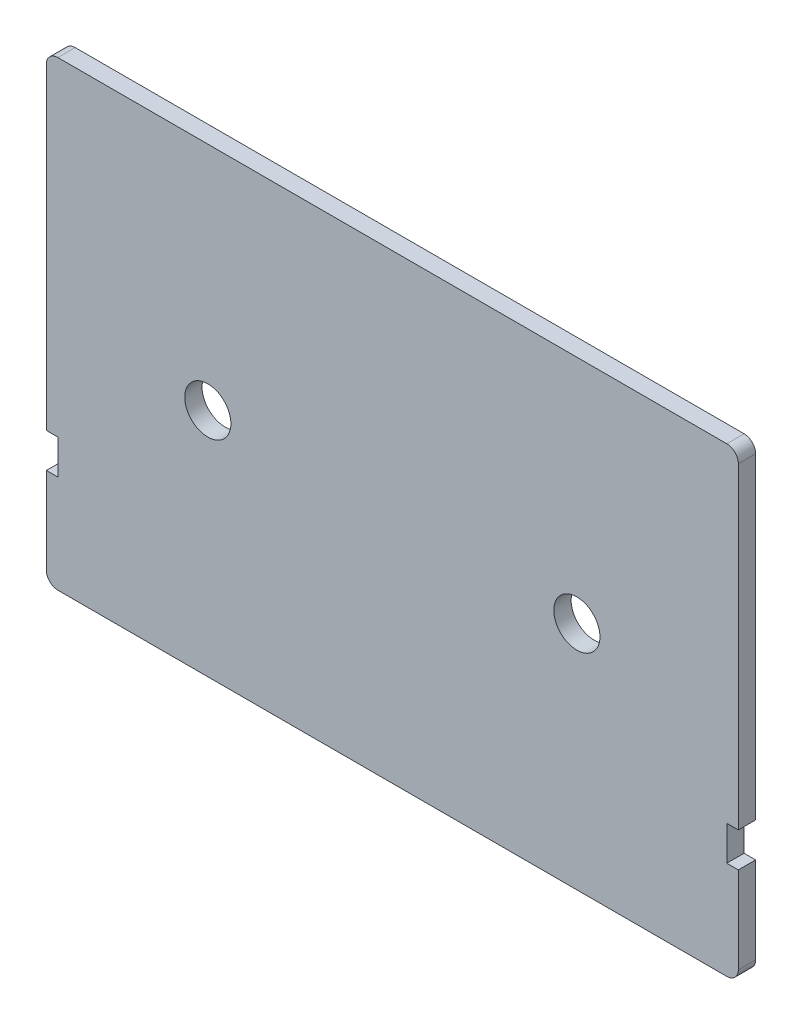
SolidWorks part; units mm, degrees
ref_plane "前视基准面" through (0, 0, 0) normal (0, 0, 1) x (1, 0, 0)
ref_plane "上视基准面" through (0, 0, 0) normal (0, 1, 0) x (1, 0, 0)
ref_plane "右视基准面" through (0, 0, 0) normal (1, 0, 0) x (0, 0, -1)
sketch "草图1" plane through (0, 0, 0) normal (0, 0, 1) x (1, 0, 0)
  line L1 (30, -20) -> (-30, -20)
  line L2 (30, -20) -> (30, 20)
  line L3 (30, 20) -> (-30, 20)
  line L4 (-30, -20) -> (-30, 20)
  line L5 (30, -20) -> (-30, 20) construction
  line L6 (30, 20) -> (-30, -20) construction
  point P0 (0, 0)
  dimension "D1" = 60
  dimension "D2" = 40
extrude "凸台-拉伸1" add sketch "草图1" along normal blind 1.5
sketch "草图3" plane through (0, 0, 1.5) normal (0, 0, 1) x (1, 0, 0)
  circle A0 centre (-16, 0) radius 2
  circle A1 centre (16, 0) radius 2
  point P4 (0, 0)
  dimension "D1" = 4
  dimension "D2" = 4
  dimension "D3" = 16
  dimension "D4" = 16
extrude "切除-拉伸1" cut sketch "草图3" against normal blind 10
sketch "草图4" plane through (0, 0, 1.5) normal (0, 0, 1) x (1, 0, 0)
  line L0 (-30, 20) -> (-30, -20) construction
  line L1 (-30, -11.5) -> (-29, -11.5)
  line L2 (-30, -11.5) -> (-30, -8.5)
  line L3 (-30, -8.5) -> (-29, -8.5)
  line L4 (-29, -11.5) -> (-29, -8.5)
  line L5 (-30, -11.5) -> (-29, -8.5) construction
  line L6 (-30, -8.5) -> (-29, -11.5) construction
  line L7 (30, -20) -> (30, 20) construction
  line L8 (30, -11.5) -> (29, -11.5)
  line L9 (30, -11.5) -> (30, -8.5)
  line L10 (30, -8.5) -> (29, -8.5)
  line L11 (29, -11.5) -> (29, -8.5)
  line L12 (30, -11.5) -> (29, -8.5) construction
  line L13 (30, -8.5) -> (29, -11.5) construction
  circle A0 centre (16, 0) radius 2 construction
  point P4 (-29.5, -10)
  point P11 (29.5, -10)
  dimension "D6" = 10
  dimension "D1" = 3
  dimension "D2" = 3
  dimension "D3" = 1
  dimension "D4" = 1
  dimension "D5" = 10
extrude "切除-拉伸2" cut sketch "草图4" against normal blind 10
fillet "圆角1" radius 1 4 edges at (-30, -20, 0.75) (30, -20, 0.75) (30, 20, 0.75) (-30, 20, 0.75)
